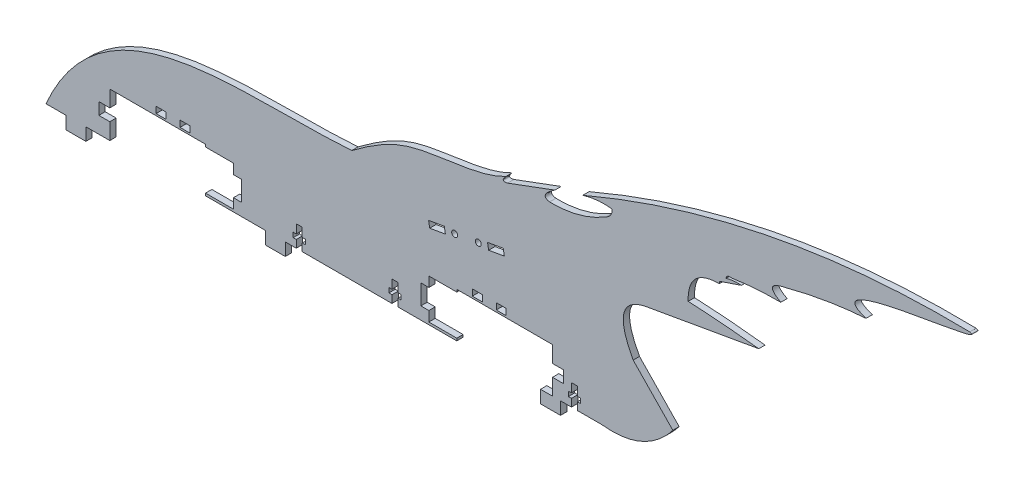
SolidWorks part; units mm, degrees
ref_plane "前视基准面" through (0, 0, 0) normal (0, 0, 1) x (1, 0, 0)
ref_plane "上视基准面" through (0, 0, 0) normal (0, 1, 0) x (1, 0, 0)
ref_plane "右视基准面" through (0, 0, 0) normal (1, 0, 0) x (0, 0, -1)
sketch "Sketch1" plane through (0, 0, 0) normal (0, 0, 1) x (1, 0, 0)
  line L0 (-360, 0) -> (360, 0) construction
  line L1 (-19.5671, 50.1455) -> (753.6757, 55.0373) construction
  line L2 (-32.114, 89.2833) -> (541.2194, 89.2833) construction
sketch "Sketch2" plane through (0, 0, 0) normal (0, 0, 1) x (1, 0, 0)
  line L0 (-171.469, -34.0766) -> (107.0727, -34.0766)
  spline S0 degree 2 poles (291.7809, 98.4714) (190.6089, 100.5394) (97.7379, 60.7759) knots 0 0 0 1 1 1
  spline S1 degree 2 poles (97.7379, 60.7759) (104.9288, 63.0011) (112.3796, 62.1565) knots 0 0 0 1 1 1
  spline S2 degree 2 poles (112.3796, 62.1565) (112.7301, 59.0518) (109.5504, 57.3117) knots 0 0 0 1 1 1
  spline S3 degree 2 poles (109.5504, 57.3117) (96.53, 49.2469) (81.0586, 49.5528) knots 0 0 0 1 1 1
  spline S4 degree 2 poles (81.0586, 49.5528) (75.6423, 50.628) (83.6966, 55.9983) knots 0 0 0 1 1 1
  spline S5 degree 1 poles (83.6966, 55.9983) (60.0234, 47.198) knots 0 0 1 1
  spline S6 degree 2 poles (60.0234, 47.198) (56.1503, 46.2452) (59.1238, 49.6133) knots 0 0 0 1 1 1
  spline S7 degree 3 poles (59.1238, 49.6133) (44.2925, 41.9215) (13.2093, 43.4053) (-7.7072, 29.9938) (-18.1066, 22.3013) knots 0 0 0 0 0.606339 1 1 1 1
  spline S8 degree 3 poles (-18.1066, 22.3013) (-73.3001, 18.1787) (-142.3815, 32.9288) (-171.469, -34.0766) knots 0 0 0 0 1 1 1 1
  spline S9 degree 2 poles (107.0727, -34.0766) (128.9682, -36.583) (142.8921, -18.7155) knots 0 0 0 1 1 1
  spline S10 degree 2 poles (166.2115, 56.6) (150.1116, 56.4482) (150.5886, 41.1327) knots 0 0 0 1 1 1
  spline S11 degree 2 poles (150.5886, 41.1327) (168.3325, 40.2418) (185.983, 38.2447) knots 0 0 0 1 1 1
  spline S12 degree 1 poles (185.983, 38.2447) (129.8121, 28.3469) knots 0 0 1 1
  spline S13 degree 2 poles (129.8121, 28.3469) (110.3675, 24.8357) (122.9996, 1.8225) knots 0 0 0 1 1 1
  spline S14 degree 1 poles (122.9996, 1.8225) (142.8921, -18.7155) knots 0 0 1 1
  spline S25 degree 1 poles (166.2115, 56.6) (166.2327, 57.6697) knots 0 0 1 1
  spline S26 degree 1 poles (166.2327, 57.6697) (177.2433, 61.4033) knots 0 0 1 1
  spline S27 degree 2 poles (177.2433, 61.4033) (173.3395, 61.7966) (169.6271, 60.6108) knots 0 0 0 1 1 1
  spline S28 degree 2 poles (169.6271, 60.6108) (169.7629, 62.5449) (172.4023, 62.1565) knots 0 0 0 1 1 1
  spline S29 degree 2 poles (172.4023, 62.1565) (184.6173, 64.0415) (197.0298, 63.9473) knots 0 0 0 1 1 1
  spline S30 degree 2 poles (197.0298, 63.9473) (187.7347, 69.0696) (198.9644, 71.4021) knots 0 0 0 1 1 1
  spline S31 degree 2 poles (198.9644, 71.4021) (219.0035, 76.7865) (239.7646, 78.3299) knots 0 0 0 1 1 1
  spline S32 degree 3 poles (291.7809, 98.4714) (303.0909, 95.7177) (210.844, 88.0264) (239.7646, 78.3299) knots 0 0 0 0 1 1 1 1
extrude "Boss-Extrude1" add sketch "Sketch2" along normal blind 3.175
sketch "Sketch3" plane through (0, 0, 3.175) normal (0, 0, 1) x (1, 0, 0)
  line L0 (-156.469, -23.0187) -> (-156.469, -49.8356) construction
  line L1 (-161.469, -34.0766) -> (-151.469, -34.0766)
  line L2 (-171.469, -34.0766) -> (107.0727, -34.0766) construction
  line L3 (-161.469, -34.0766) -> (-161.469, -40.4266)
  line L4 (-161.469, -40.4266) -> (-151.469, -40.4266)
  line L5 (-151.469, -40.4266) -> (-151.469, -34.0766)
  line L6 (-106.469, -7.8183) -> (-106.469, -55.0925) construction
  line L7 (-56.469, -23.0187) -> (-56.469, -49.8356) construction
  line L8 (-61.469, -40.4266) -> (-61.469, -34.0766)
  line L9 (-51.469, -40.4266) -> (-61.469, -40.4266)
  line L10 (-51.469, -34.0766) -> (-51.469, -40.4266)
  line L11 (-51.469, -34.0766) -> (-61.469, -34.0766)
  line L12 (-37.469, -5.6354) -> (-37.469, -55.0925) construction
  line L13 (81.531, -23.0187) -> (81.531, -49.8356) construction
  line L14 (76.531, -40.4266) -> (76.531, -34.0766)
  line L15 (86.531, -40.4266) -> (76.531, -40.4266)
  line L16 (86.531, -34.0766) -> (86.531, -40.4266)
  line L17 (86.531, -34.0766) -> (76.531, -34.0766)
  point P6 (-156.469, -34.0766)
  dimension "D1" = 10
  dimension "D2" = 15
  dimension "D3" = 6.35
  dimension "D4" = 100
  dimension "D5" = 238
extrude "Boss-Extrude2" add sketch "Sketch3" against normal blind 3.175
sketch "Sketch4" plane through (0, 0, 0) normal (0, 0, 1) x (1, 0, 0)
  line L0 (-8.7353, 21.0767) -> (49.2725, 25.4437)
  spline S0 degree 3 poles (55.4358, 40.7209) (33.0546, 40.3601) (7.8741, 39.273) (-8.7353, 21.0767) knots 0 0 0 0 1 1 1 1
  spline S1 degree 3 poles (55.4358, 40.7209) (56.7107, 34.9555) (51.7522, 29.9519) (49.2725, 25.4437) knots 0 0 0 0 1 1 1 1
extrude "Cut-Extrude1" cut sketch "Sketch4" along normal blind 1
sketch "Sketch5" plane through (0, 0, 3.175) normal (0, 0, 1) x (1, 0, 0)
  line L0 (-44.469, -4.9545) -> (-44.469, -56.9042) construction
  line L1 (-45.969, -34.0766) -> (-42.969, -34.0766)
  line L2 (-151.469, -34.0766) -> (-61.469, -34.0766) construction
  line L3 (-45.969, -34.0766) -> (-45.969, -30.2766)
  line L4 (-45.969, -23.4266) -> (-42.969, -23.4266)
  line L5 (-42.969, -23.4266) -> (-42.969, -27.8766)
  line L6 (-161.469, -40.4266) -> (-151.469, -40.4266) construction
  line L7 (-41.419, -27.8766) -> (-41.419, -30.2766)
  line L8 (-47.519, -27.8766) -> (-47.519, -30.2766)
  line L9 (-47.519, -27.8766) -> (-45.969, -27.8766)
  line L10 (-47.519, -30.2766) -> (-45.969, -30.2766)
  line L11 (-47.519, -29.0766) -> (-93.8427, -29.0766) construction
  line L12 (-161.469, -34.0766) -> (-161.469, -40.4266) construction
  line L13 (-42.969, -27.8766) -> (-41.419, -27.8766)
  line L14 (-42.969, -30.2766) -> (-41.419, -30.2766)
  line L15 (-45.969, -27.8766) -> (-45.969, -23.4266)
  line L16 (-42.969, -30.2766) -> (-42.969, -34.0766)
  line L17 (-20.469, -10.7451) -> (-20.469, -65.5516) construction
  line L18 (3.531, -4.9545) -> (3.531, -56.9042) construction
  line L19 (2.031, -30.2766) -> (2.031, -34.0766)
  line L20 (5.031, -27.8766) -> (5.031, -23.4266)
  line L21 (2.031, -30.2766) -> (0.481, -30.2766)
  line L22 (2.031, -27.8766) -> (0.481, -27.8766)
  line L23 (6.581, -30.2766) -> (5.031, -30.2766)
  line L24 (6.581, -27.8766) -> (5.031, -27.8766)
  line L25 (6.581, -27.8766) -> (6.581, -30.2766)
  line L26 (0.481, -27.8766) -> (0.481, -30.2766)
  line L27 (2.031, -23.4266) -> (2.031, -27.8766)
  line L28 (5.031, -23.4266) -> (2.031, -23.4266)
  line L29 (5.031, -34.0766) -> (5.031, -30.2766)
  line L30 (5.031, -34.0766) -> (2.031, -34.0766)
  line L31 (24.531, -8.6696) -> (24.531, -64.6722) construction
  line L32 (93.531, -4.9545) -> (93.531, -56.9042) construction
  line L33 (92.031, -30.2766) -> (92.031, -34.0766)
  line L34 (95.031, -27.8766) -> (95.031, -23.4266)
  line L35 (92.031, -30.2766) -> (90.481, -30.2766)
  line L36 (92.031, -27.8766) -> (90.481, -27.8766)
  line L37 (96.581, -30.2766) -> (95.031, -30.2766)
  line L38 (96.581, -27.8766) -> (95.031, -27.8766)
  line L39 (96.581, -27.8766) -> (96.581, -30.2766)
  line L40 (90.481, -27.8766) -> (90.481, -30.2766)
  line L41 (92.031, -23.4266) -> (92.031, -27.8766)
  line L42 (95.031, -23.4266) -> (92.031, -23.4266)
  line L43 (95.031, -34.0766) -> (95.031, -30.2766)
  line L44 (95.031, -34.0766) -> (92.031, -34.0766)
  point P6 (-44.469, -34.0766)
  dimension "D1" = 3
  dimension "D2" = 17
  dimension "D3" = 6.1
  dimension "D4" = 5
  dimension "D5" = 117
  dimension "D6" = 2.4
  dimension "D7" = 165
  dimension "D8" = 255
extrude "Cut-Extrude2" cut sketch "Sketch5" against normal through all
sketch "Sketch7" plane through (0, 0, 3.175) normal (0, 0, 1) x (1, 0, 0)
  line L0 (-91.469, -32.8766) -> (-77.469, -32.8766)
  line L1 (-139.469, -34.0766) -> (-139.469, -25.8766)
  line L2 (-151.469, -34.0766) -> (-61.469, -34.0766) construction
  line L3 (-139.469, -11.6766) -> (-91.469, -11.6766)
  line L4 (-91.469, -11.6766) -> (-91.469, -12.8766)
  line L5 (-139.469, -34.0766) -> (-91.469, -34.0766)
  line L6 (-155.6863, -22.8766) -> (-79.2758, -22.8766) construction
  line L7 (-91.469, -12.8766) -> (-77.469, -12.8766)
  line L8 (-77.469, -12.8766) -> (-77.469, -17.8766)
  line L9 (-91.469, -32.8766) -> (-91.469, -34.0766)
  line L10 (-139.469, -19.8766) -> (-144.969, -19.8766)
  line L11 (-139.469, -25.8766) -> (-144.969, -25.8766)
  line L12 (-144.969, -19.8766) -> (-144.969, -25.8766)
  line L13 (-139.469, -19.8766) -> (-139.469, -11.6766)
  line L14 (-77.469, -17.8766) -> (-73.469, -17.8766)
  line L15 (-77.469, -27.8766) -> (-73.469, -27.8766)
  line L16 (-73.469, -17.8766) -> (-73.469, -27.8766)
  line L17 (-77.469, -27.8766) -> (-77.469, -32.8766)
  line L18 (-28.469, 4.1122) -> (-28.469, -62.6854) construction
  line L19 (98.7482, -22.8766) -> (22.3377, -22.8766) construction
  line L20 (20.531, -27.8766) -> (20.531, -32.8766)
  line L21 (16.531, -17.8766) -> (16.531, -27.8766)
  line L22 (20.531, -27.8766) -> (16.531, -27.8766)
  line L23 (20.531, -17.8766) -> (16.531, -17.8766)
  line L24 (82.531, -19.8766) -> (82.531, -11.6766)
  line L25 (88.031, -19.8766) -> (88.031, -25.8766)
  line L26 (82.531, -25.8766) -> (88.031, -25.8766)
  line L27 (82.531, -19.8766) -> (88.031, -19.8766)
  line L28 (34.531, -32.8766) -> (34.531, -34.0766)
  line L29 (20.531, -12.8766) -> (20.531, -17.8766)
  line L30 (34.531, -12.8766) -> (20.531, -12.8766)
  line L31 (82.531, -34.0766) -> (34.531, -34.0766)
  line L32 (34.531, -11.6766) -> (34.531, -12.8766)
  line L33 (82.531, -11.6766) -> (34.531, -11.6766)
  line L34 (82.531, -34.0766) -> (82.531, -25.8766)
  line L35 (34.531, -32.8766) -> (20.531, -32.8766)
  line L36 (-120.2067, -9.1491) -> (-44.1643, -9.1491) construction
  line L37 (-107.769, -0.3828) -> (-107.769, -8.179) construction
  line L38 (-111.269, -10.7366) -> (-116.269, -10.7366)
  line L39 (-111.269, -10.7366) -> (-111.269, -7.5616)
  line L40 (-111.269, -7.5616) -> (-116.269, -7.5616)
  line L41 (-116.269, -10.7366) -> (-116.269, -7.5616)
  line L42 (-111.269, -10.7366) -> (-116.269, -7.5616) construction
  line L43 (-111.269, -7.5616) -> (-116.269, -10.7366) construction
  line L44 (-104.269, -7.5616) -> (-99.269, -10.7366) construction
  line L45 (-104.269, -10.7366) -> (-99.269, -7.5616) construction
  line L46 (-99.269, -10.7366) -> (-99.269, -7.5616)
  line L47 (-104.269, -7.5616) -> (-99.269, -7.5616)
  line L48 (-104.269, -10.7366) -> (-104.269, -7.5616)
  line L49 (-104.269, -10.7366) -> (-99.269, -10.7366)
  line L50 (47.331, -10.7366) -> (42.331, -7.5616) construction
  line L51 (47.331, -7.5616) -> (42.331, -10.7366) construction
  line L52 (54.331, -7.5616) -> (59.331, -10.7366) construction
  line L53 (54.331, -10.7366) -> (59.331, -7.5616) construction
  line L54 (47.331, -10.7366) -> (42.331, -10.7366)
  line L55 (47.331, -10.7366) -> (47.331, -7.5616)
  line L56 (47.331, -7.5616) -> (42.331, -7.5616)
  line L57 (42.331, -10.7366) -> (42.331, -7.5616)
  line L58 (59.331, -10.7366) -> (59.331, -7.5616)
  line L59 (54.331, -7.5616) -> (59.331, -7.5616)
  line L60 (54.331, -10.7366) -> (54.331, -7.5616)
  line L61 (54.331, -10.7366) -> (59.331, -10.7366)
  point P43 (-113.769, -9.1491)
  point P54 (-101.769, -9.1491)
  point P63 (44.831, -9.1491)
  point P64 (56.831, -9.1491)
  dimension "D3" = 48
  dimension "D1" = 32
  dimension "D2" = 22.4
  dimension "D4" = 20
  dimension "D5" = 14
  dimension "D6" = 6
  dimension "D7" = 5.5
  dimension "D8" = 4
  dimension "D9" = 10
  dimension "D10" = 90
  dimension "D11" = 12
  dimension "D12" = 23.2
  dimension "D13" = 0.94
  dimension "D14" = 3.175
  dimension "D15" = 5
extrude "Cut-Extrude3" cut sketch "Sketch7" against normal through all
sketch "Sketch8" plane through (0, 0, 0) normal (0, 0, -1) x (-1, 0, 0)
  line L0 (0, 0) -> (0, 6) construction
  line L1 (0, 6) -> (-41.3619, 13.2932) construction
  line L2 (-39.3923, 12.9459) -> (-37.8172, 21.8786) construction
  line L3 (-20.4053, 11.21) -> (-20.9566, 8.0832)
  line L4 (-20.9566, 8.0832) -> (-28.8351, 9.4724)
  line L5 (-28.8351, 9.4724) -> (-28.2838, 12.5992)
  line L6 (-28.2838, 12.5992) -> (-20.4053, 11.21)
  line L7 (-24.3445, 11.9046) -> (-23.2344, 18.2003) construction
  line L10 (-49.9495, 16.4194) -> (-50.5009, 13.2927)
  line L12 (-58.3793, 14.6819) -> (-50.5009, 13.2927)
  line L13 (-53.8888, 17.114) -> (-52.7787, 23.4098) construction
  line L14 (-58.3793, 14.6819) -> (-57.828, 17.8086)
  line L15 (-49.9495, 16.4194) -> (-57.828, 17.8086)
  circle A0 centre (-33.4835, 11.904) radius 1.5
  circle A1 centre (-45.3012, 13.9878) radius 1.5
  point P10 (-20.681, 9.6466)
  dimension "D7" = 3
  dimension "D1" = 6
  dimension "D2" = 100
  dimension "D3" = 40
  dimension "D4" = 8
  dimension "D5" = 3.175
  dimension "D6" = 30
  dimension "D8" = 12
extrude "Cut-Extrude4" cut sketch "Sketch8" against normal through all
